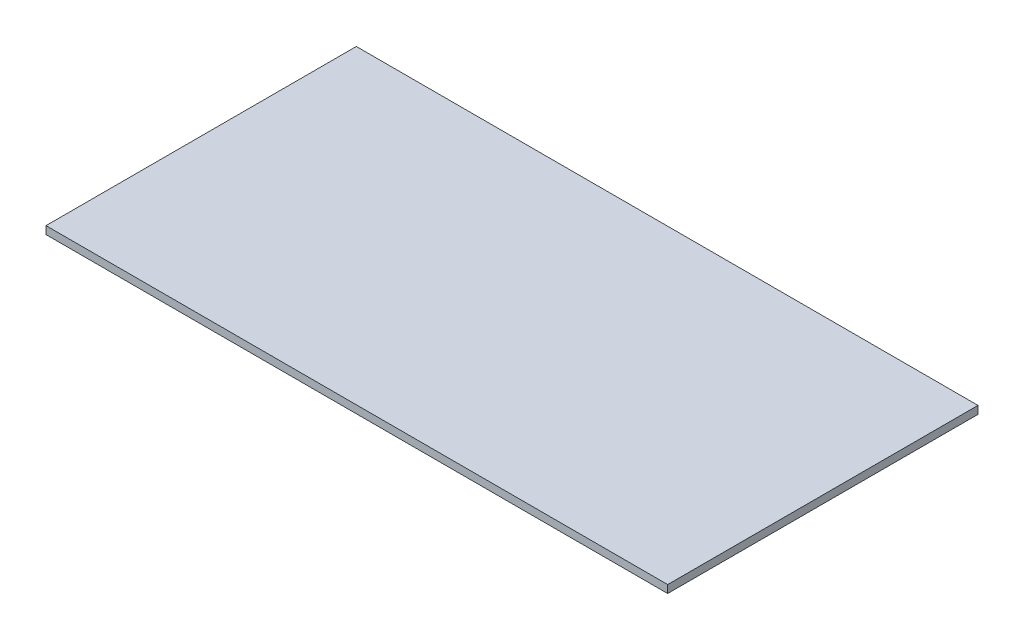
SolidWorks part; units mm, degrees
ref_plane "Front Plane" through (0, 0, 0) normal (0, 0, 1) x (1, 0, 0)
ref_plane "Top Plane" through (0, 0, 0) normal (0, 1, 0) x (1, 0, 0)
ref_plane "Right Plane" through (0, 0, 0) normal (1, 0, 0) x (0, 0, -1)
sketch "Sketch1" plane through (0, 0, 0) normal (0, 1, 0) x (1, 0, 0)
  line L1 (-1198, -598) -> (1198, -598)
  line L2 (-1198, -598) -> (-1198, 598)
  line L3 (-1198, 598) -> (1198, 598)
  line L4 (1198, -598) -> (1198, 598)
  line L5 (-1198, -598) -> (1198, 598) construction
  line L6 (-1198, 598) -> (1198, -598) construction
  point P0 (0, 0)
  dimension "D1" = 1196
  dimension "D2" = 2396
extrude "Boss-Extrude1" add sketch "Sketch1" along normal blind 30
